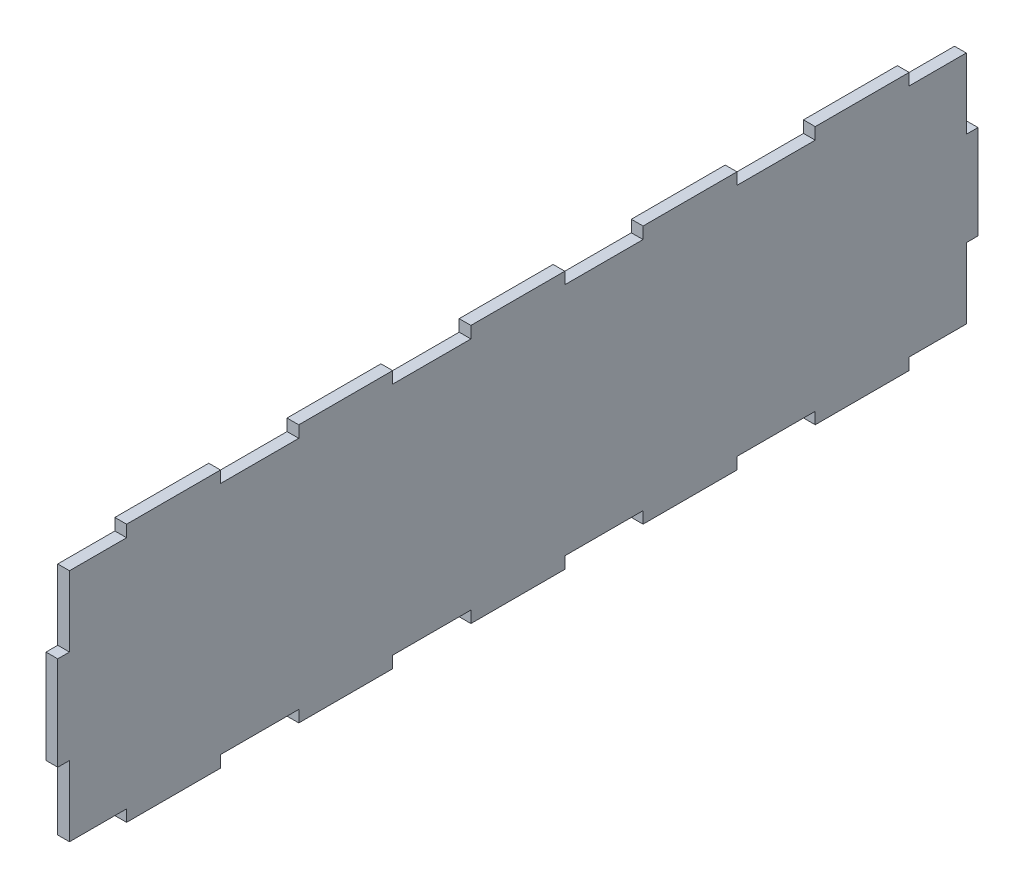
SolidWorks part; units mm, degrees
material "Maple"
ref_plane "Front Plane" through (0, 0, 0) normal (0, 0, 1) x (1, 0, 0)
ref_plane "Top Plane" through (0, 0, 0) normal (0, 1, 0) x (1, 0, 0)
ref_plane "Right Plane" through (0, 0, 0) normal (1, 0, 0) x (0, 0, -1)
sketch "Sketch1" plane through (0, 0, 0) normal (1, 0, 0) x (0, 0, -1)
  line L0 (-98, -27.5) -> (-98, 27.5) construction
  line L1 (-95.5, -25) -> (95.5, -25) construction
  line L2 (-95.5, -25) -> (-95.5, 25) construction
  line L3 (-95.5, 25) -> (95.5, 25) construction
  line L4 (95.5, -25) -> (95.5, 25) construction
  line L5 (-95.5, -25) -> (95.5, 25) construction
  line L6 (-95.5, 25) -> (95.5, -25) construction
  line L7 (-98, 27.5) -> (98, 27.5) construction
  line L8 (98, -27.5) -> (98, 27.5) construction
  line L9 (-98, -27.5) -> (98, -27.5) construction
  line L10 (-100, 22.5) -> (-100, -22.5) construction
  line L11 (0, -12.7783) -> (0, 11.2959) construction
  line L12 (100, 22.5) -> (100, -22.5) construction
  line L13 (10, -27.5) -> (-10, -27.5)
  line L14 (-10, -27.5) -> (-10, -25)
  line L15 (-10, -25) -> (-26.6667, -25)
  line L16 (-26.6667, -25) -> (-26.6667, -27.5)
  line L17 (-26.6667, -27.5) -> (-46.6667, -27.5)
  line L18 (-46.6667, -27.5) -> (-46.6667, -25)
  line L19 (-46.6667, -25) -> (-63.3333, -25)
  line L20 (-63.3333, -25) -> (-63.3333, -27.5)
  line L21 (-63.3333, -27.5) -> (-83.3333, -27.5)
  line L22 (-83.3333, -27.5) -> (-83.3333, -25)
  line L23 (-83.3333, -25) -> (-95.5, -25)
  line L24 (-95.5, -25) -> (-95.5, -10)
  line L25 (-95.5, -10) -> (-98, -10)
  line L26 (-98, -10) -> (-98, 10)
  line L27 (-19.2126, 0) -> (21.2755, 0) construction
  line L28 (-95.5, 10) -> (-98, 10)
  line L29 (-95.5, 25) -> (-95.5, 10)
  line L30 (-83.3333, 25) -> (-95.5, 25)
  line L31 (-83.3333, 27.5) -> (-83.3333, 25)
  line L32 (-63.3333, 27.5) -> (-83.3333, 27.5)
  line L33 (-63.3333, 25) -> (-63.3333, 27.5)
  line L34 (-46.6667, 25) -> (-63.3333, 25)
  line L35 (-46.6667, 27.5) -> (-46.6667, 25)
  line L36 (-26.6667, 27.5) -> (-46.6667, 27.5)
  line L37 (-26.6667, 25) -> (-26.6667, 27.5)
  line L38 (-10, 25) -> (-26.6667, 25)
  line L39 (-10, 27.5) -> (-10, 25)
  line L40 (10, 27.5) -> (-10, 27.5)
  line L41 (10, 27.5) -> (10, 25)
  line L42 (10, 25) -> (26.6667, 25)
  line L43 (26.6667, 25) -> (26.6667, 27.5)
  line L44 (26.6667, 27.5) -> (46.6667, 27.5)
  line L45 (46.6667, 27.5) -> (46.6667, 25)
  line L46 (46.6667, 25) -> (63.3333, 25)
  line L47 (63.3333, 25) -> (63.3333, 27.5)
  line L48 (63.3333, 27.5) -> (83.3333, 27.5)
  line L49 (83.3333, 27.5) -> (83.3333, 25)
  line L50 (83.3333, 25) -> (95.5, 25)
  line L51 (95.5, 25) -> (95.5, 10)
  line L52 (95.5, 10) -> (98, 10)
  line L53 (98, -10) -> (98, 10)
  line L54 (95.5, -10) -> (98, -10)
  line L55 (95.5, -25) -> (95.5, -10)
  line L56 (83.3333, -25) -> (95.5, -25)
  line L57 (83.3333, -27.5) -> (83.3333, -25)
  line L58 (63.3333, -27.5) -> (83.3333, -27.5)
  line L59 (63.3333, -25) -> (63.3333, -27.5)
  line L60 (46.6667, -25) -> (63.3333, -25)
  line L61 (46.6667, -27.5) -> (46.6667, -25)
  line L62 (26.6667, -27.5) -> (46.6667, -27.5)
  line L63 (26.6667, -25) -> (26.6667, -27.5)
  line L64 (10, -25) -> (26.6667, -25)
  line L65 (10, -27.5) -> (10, -25)
  line L66 (-83.3333, 25) -> (-100, 25)
  point P0 (0, 0)
  point P16 (-98, 20)
  point P33 (-98, 0)
  point P46 (0, 27.5)
  point P69 (0, -27.5)
  point P71 (0, 0)
  point P72 (-100, 20)
  dimension "D1" = 191
  dimension "D2" = 50
  dimension "D4" = 100
  dimension "D5" = 20
  dimension "D3" = 2.5
extrude "Boss-Extrude1" add sketch "Sketch1" along normal mid plane 2.5 contours L13 L65 L64 L63 L62 L61 L60 L59 L58 L57 L56 L55 L54 L53 L52 L51 L50 L49 L48 L47 L46 L45 L44 L43 L42 L41 L40 L39 L38 L37 L36 L35 L34 L33 L32 L31 L30 L29 L28 L26 L25 L24 L23 L22 L21 L20 L19 L18 L17 L16 L15
